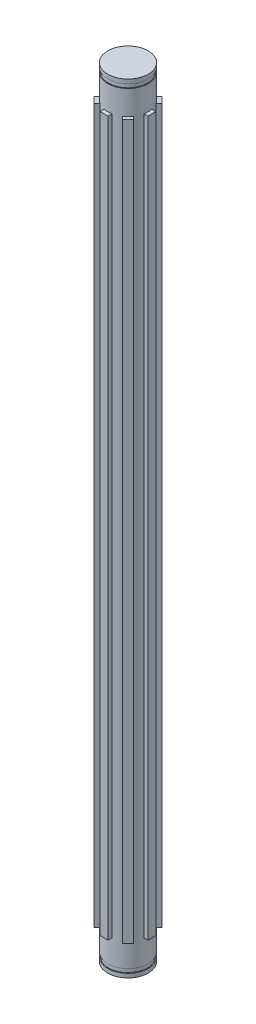
SolidWorks part; units mm, degrees
material "PE High Density"
ref_plane "Front Plane" through (0, 0, 0) normal (0, 0, 1) x (1, 0, 0)
ref_plane "Top Plane" through (0, 0, 0) normal (0, 1, 0) x (1, 0, 0)
ref_plane "Right Plane" through (0, 0, 0) normal (1, 0, 0) x (0, 0, -1)
sketch "Sketch3" plane through (0, 0, 0) normal (1, 0, 0) x (0, 0, -1)
  line L0 (0, 96) -> (5, 96)
  line L1 (0, 0) -> (5, 0)
  line L2 (0, 0) -> (0, 96)
  line L4 (5, 0) -> (5, 96)
  line L5 (5, 1) -> (4.8, 1)
  line L6 (5, 1) -> (5, 2)
  line L7 (5, 2) -> (4.8, 2)
  line L8 (4.8, 1) -> (4.8, 2)
  line L17 (2.5, 2) -> (2.5, 8) construction
  line L18 (0, 2) -> (5, 2) construction
  line L19 (0, 8) -> (5, 8) construction
  dimension "D1" = 6
  dimension "D2" = 5
  dimension "D3" = 4.8
  dimension "D4" = 1
  dimension "D5" = 1
  dimension "D6" = 88
revolve "Revolve1" add sketch "Sketch3" angle 360 about L2
sketch "Sketch4" plane through (0, 0, 0) normal (0, -1, 0) x (1, 0, 0)
  line L0 (-1, 4.899) -> (-1, 5.899)
  line L1 (-1, 5.899) -> (1, 5.899)
  line L2 (1, 5.899) -> (1, 4.899)
  line L3 (0, 0) -> (0, 15.0182) construction
  circle A0 centre (0, 0) radius 5 construction
  arc A1 (-1, 4.899) -> (1, 4.899) centre (0, 0) cw
  circle M6 centre (0, 0) radius 5
  dimension "D1" = 2
  dimension "D2" = 1
extrude "Boss-Extrude2" add sketch "Sketch4" against normal through all from vertex at -8 contours A1 L3 L1 L0 | L3 L2 L1 M6 starting at point (0, 8, -5)
pattern_circular "CirPattern1" count 8 over 360 about axis through (0, 0, 0) along (0, 1, 0) of "Boss-Extrude2"
mirror "Mirror1" about plane through (0, 96, 0) normal (0, -1, 0) of bodies 104 102
